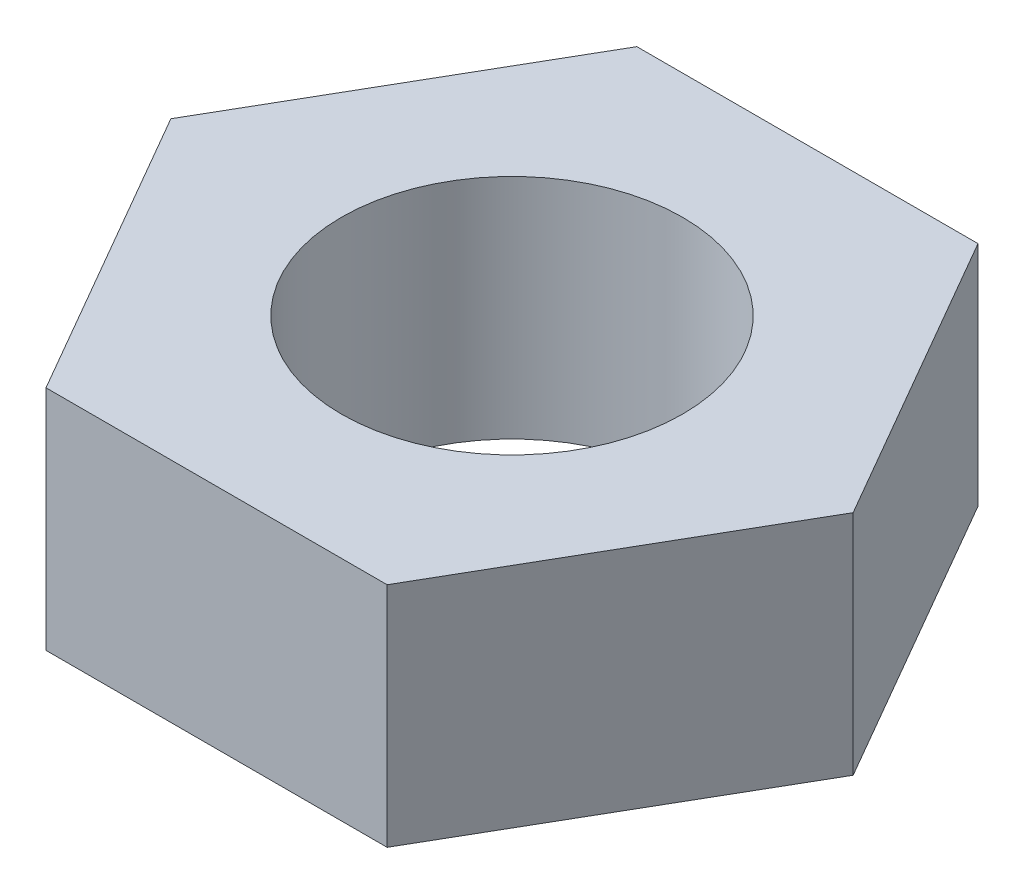
SolidWorks part; units mm, degrees
ref_plane "Front Plane" through (0, 0, 0) normal (0, 0, 1) x (1, 0, 0)
ref_plane "Top Plane" through (0, 0, 0) normal (0, 1, 0) x (1, 0, 0)
ref_plane "Right Plane" through (0, 0, 0) normal (1, 0, 0) x (0, 0, -1)
sketch "Sketch1" plane through (0, 0, 0) normal (0, 1, 0) x (1, 0, 0)
  line L1 (3, 0) -> (1.5, 2.5981)
  line L2 (1.5, 2.5981) -> (-1.5, 2.5981)
  line L3 (-1.5, 2.5981) -> (-3, 0)
  line L4 (-3, 0) -> (-1.5, -2.5981)
  line L5 (-1.5, -2.5981) -> (1.5, -2.5981)
  line L6 (1.5, -2.5981) -> (3, 0)
  circle A0 centre (0, 0) radius 3 construction
  circle A1 centre (0, 0) radius 1.5
extrude "Boss-Extrude1" add sketch "Sketch1" along normal blind 2
